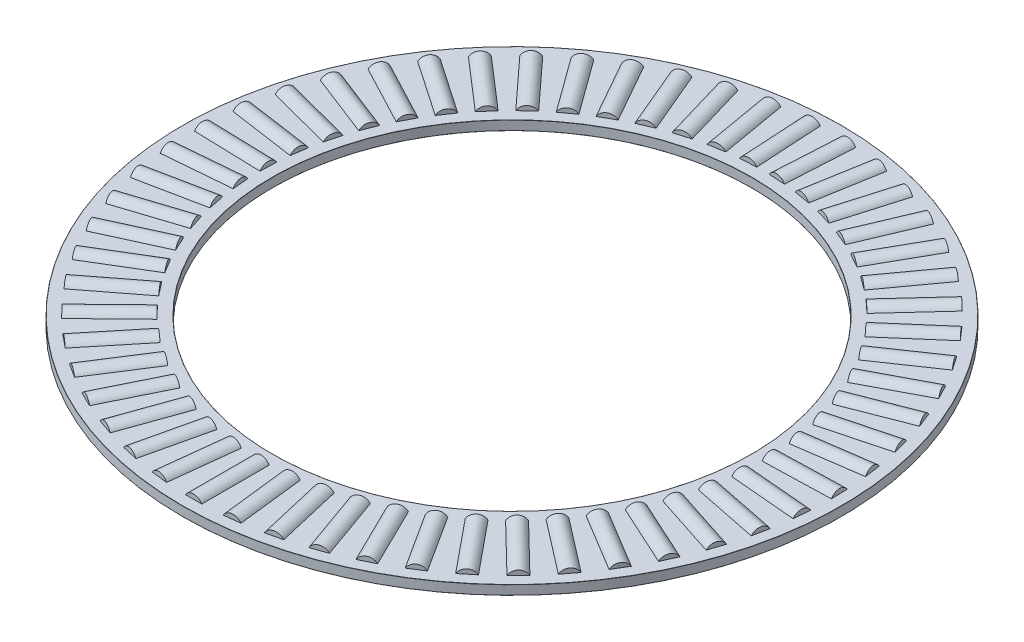
SolidWorks part; units mm, degrees
ref_plane "Front Plane" through (0, 0, 0) normal (0, 0, 1) x (1, 0, 0)
ref_plane "Top Plane" through (0, 0, 0) normal (0, 1, 0) x (1, 0, 0)
ref_plane "Right Plane" through (0, 0, 0) normal (1, 0, 0) x (0, 0, -1)
sketch "Sketch1" plane through (0, 0, 0) normal (1, 0, 0) x (0, 0, -1)
  line L0 (-34.925, 0) -> (34.925, 0) construction
  line L1 (0, -0.9922) -> (0, 0.9922) construction
  line L2 (-34.925, 0.4961) -> (-25.4, 0.4961)
  line L3 (-34.925, 0.4961) -> (-34.925, -0.4961)
  line L4 (-34.925, -0.4961) -> (-25.4, -0.4961)
  line L5 (-25.4, 0.4961) -> (-25.4, -0.4961)
  line L7 (-30.1625, 0.9922) -> (-30.1625, 0.4961) construction
  line L8 (-33.7344, 0.9922) -> (-26.5906, 0.9922) construction
  line L9 (-33.7344, 0.9922) -> (-33.7344, -0.9922) construction
  line L10 (-33.7344, -0.9922) -> (-26.5906, -0.9922) construction
  line L11 (-26.5906, 0.9922) -> (-26.5906, -0.9922) construction
  point P16 (-33.7344, 0)
  dimension "OD" = 69.85
  dimension "Shaft Dia" = 50.8
  dimension "Th" = 1.9844
  dimension "D2" = 0.9922
  dimension "D1" = 7.1437
  dimension "D3" = 9.525
revolve "Revolve1" add sketch "Sketch1" angle 360 about L1
sketch "Sketch3" plane through (0, 0, 0) normal (1, 0, 0) x (0, 0, -1)
  line L0 (-33.7344, 0.9922) -> (-33.7344, -0.9922) construction
  line L1 (-33.7344, 0) -> (-26.5906, 0)
  line L2 (-33.7344, 0) -> (-33.7344, 0.9922)
  line L3 (-33.7344, 0.9922) -> (-26.5906, 0.9922)
  line L4 (-26.5906, 0) -> (-26.5906, 0.9922)
revolve "Cut-Revolve1" cut sketch "Sketch3" angle 360 about L1
sketch "Sketch2" plane through (0, 0, 0) normal (1, 0, 0) x (0, 0, -1)
  line L1 (-33.7344, 0) -> (-26.5906, 0)
  line L2 (-33.7344, 0) -> (-33.7344, 0.9922)
  line L3 (-33.7344, 0.9922) -> (-26.5906, 0.9922)
  line L4 (-26.5906, 0) -> (-26.5906, 0.9922)
revolve "Revolve2" add sketch "Sketch2" angle 360 about L1
ref_axis "Axis1" through (0, 0.9922, 0) along (0, -1, 0)
pattern_circular "CirPattern1" count 55 every 6.545 about axis through (0, 0.9922, 0) along (0, -1, 0) of bodies 187 411
pattern_circular "CirPattern2" count 55 every 6.545 about axis through (0, 0, 0) along (0, 1, 0) of "Cut-Revolve1"
sketch "Sketch4" plane through (0, 0, 0) normal (1, 0, 0) x (0, 0, -1)
  line L0 (-34.925, 0.4961) -> (-34.925, -0.4961) construction
  line L1 (-34.925, 9.1091) -> (-25.4, 9.1091)
  line L2 (-34.925, 9.1091) -> (-34.925, 9.9219)
  line L3 (-34.925, 9.9219) -> (-25.4, 9.9219)
  line L4 (-25.4, 9.1091) -> (-25.4, 9.9219)
  line L5 (-34.925, -9.9219) -> (-25.4, -9.9219)
  line L6 (-34.925, -9.9219) -> (-34.925, -9.1091)
  line L7 (-34.925, -9.1091) -> (-25.4, -9.1091)
  line L8 (-25.4, -9.9219) -> (-25.4, -9.1091)
  line L10 (-25.4, 0.4961) -> (-25.4, -0.4961) construction
  line L11 (0, 0) -> (-34.925, 0) construction
  line L12 (-34.925, 0) -> (34.925, 0) construction
  line L13 (0, -0.9922) -> (0, 0.9922) construction
  dimension "Ht" = 19.8438
  dimension "Washer Th" = 0.8128
  dimension "Washer ID" = 50.8
  dimension "Washer OD" = 69.85
revolve "Revolve3" [suppressed] add sketch "Sketch4" angle 360 about L1
fillet "Fillet1" [suppressed] radius 0.0198
fillet "Fillet2" radius 0.0198 4 edges at (0, -0.4961, -25.4) (0, 0.4961, -25.4) (0, -0.4961, -34.925) (0, 0.4961, -34.925)
fillet "Fillet3" [suppressed] radius 0.0198
equation "\"D2@Sketch1\" = \"Th@Sketch1\"*.5"
equation "\"D1@Fillet1\" = \"Th@Sketch1\"*.01"
equation "\"D1@Fillet2\" = \"D1@Fillet1\""
equation "\"D1@Fillet3\" = \"D1@Fillet1\""
equation "\"D1@Sketch1\" = \"D3@Sketch1\"*.75"
equation "\"Angle@CirPattern1\" = 360/\"Rollers@CirPattern1\""
equation "\"Rollers@CirPattern1\" = \"OD@Sketch1\"*20"
equation "\"D1@CirPattern2\" = \"Rollers@CirPattern1\""
equation "\"D2@CirPattern2\" = \"Angle@CirPattern1\""
equation "\"Ht@Sketch4\" = \"Th@Sketch1\"*10"
